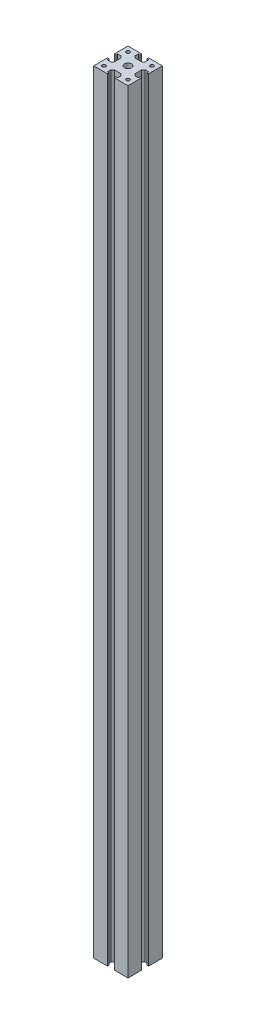
SolidWorks part; units mm, degrees
ref_plane "Front Plane" through (0, 0, 0) normal (0, 0, 1) x (1, 0, 0)
ref_plane "Top Plane" through (0, 0, 0) normal (0, 1, 0) x (1, 0, 0)
ref_plane "Right Plane" through (0, 0, 0) normal (1, 0, 0) x (0, 0, -1)
sketch "草圖1" plane through (0, 0, 0) normal (0, 1, 0) x (1, 0, 0)
  line L5 (0, 0) -> (0, 10) construction
  line L11 (-10, -10) -> (-2, -10)
  line L26 (-10, -10) -> (-10, -2)
  line L27 (-10, 10) -> (-2, 10)
  line L28 (10, -10) -> (10, -2)
  line L29 (-10, -10) -> (10, 10) construction
  line L30 (-10, 10) -> (10, -10) construction
  line L31 (-2, 10) -> (-2, 9)
  line L32 (-2, 9) -> (-3, 9)
  line L33 (-3, 9) -> (-3, 7)
  line L34 (-3, 7) -> (-2, 6)
  line L47 (-2, 6) -> (2, 6)
  line L48 (3, 7) -> (2, 6)
  line L49 (3, 9) -> (3, 7)
  line L50 (2, 10) -> (2, 9)
  line L51 (2, 9) -> (3, 9)
  line L52 (9, 3) -> (7, 3)
  line L53 (9, 2) -> (9, 3)
  line L54 (10, 2) -> (9, 2)
  line L55 (7, 3) -> (6, 2)
  line L56 (6, 2) -> (6, -2)
  line L57 (7, -3) -> (6, -2)
  line L58 (9, -3) -> (7, -3)
  line L59 (9, -2) -> (9, -3)
  line L60 (10, -2) -> (9, -2)
  line L61 (3, -9) -> (3, -7)
  line L62 (2, -9) -> (3, -9)
  line L63 (2, -10) -> (2, -9)
  line L64 (3, -7) -> (2, -6)
  line L65 (2, -6) -> (-2, -6)
  line L66 (-3, -7) -> (-2, -6)
  line L67 (-3, -9) -> (-3, -7)
  line L68 (-2, -9) -> (-3, -9)
  line L69 (-2, -10) -> (-2, -9)
  line L70 (-9, -3) -> (-7, -3)
  line L71 (-9, -2) -> (-9, -3)
  line L72 (-10, -2) -> (-9, -2)
  line L73 (-7, -3) -> (-6, -2)
  line L74 (-6, -2) -> (-6, 2)
  line L75 (-7, 3) -> (-6, 2)
  line L76 (-9, 3) -> (-7, 3)
  line L77 (-9, 2) -> (-9, 3)
  line L78 (-10, 2) -> (-9, 2)
  line L79 (2, 10) -> (10, 10)
  line L80 (-10, 2) -> (-10, 10)
  line L81 (10, 2) -> (10, 10)
  line L82 (2, -10) -> (10, -10)
  circle A5 centre (0, 0) radius 2
  circle A6 centre (-7, 7) radius 1
  circle A7 centre (7, 7) radius 1
  circle A8 centre (7, -7) radius 1
  circle A9 centre (-7, -7) radius 1
  point P0 (0, 0)
  point P15 (0, 6)
  point P60 (0, 0)
  dimension "D3" = 4
  dimension "D10" = 2
  dimension "D2" = 20
  dimension "D4" = 2
  dimension "D5" = 1
  dimension "D6" = 2
  dimension "D7" = 1
  dimension "D8" = 135
  dimension "D9" = 1
  dimension "D11" = 3
extrude "填料-伸長1" add sketch "草圖1" along normal mid plane 450
